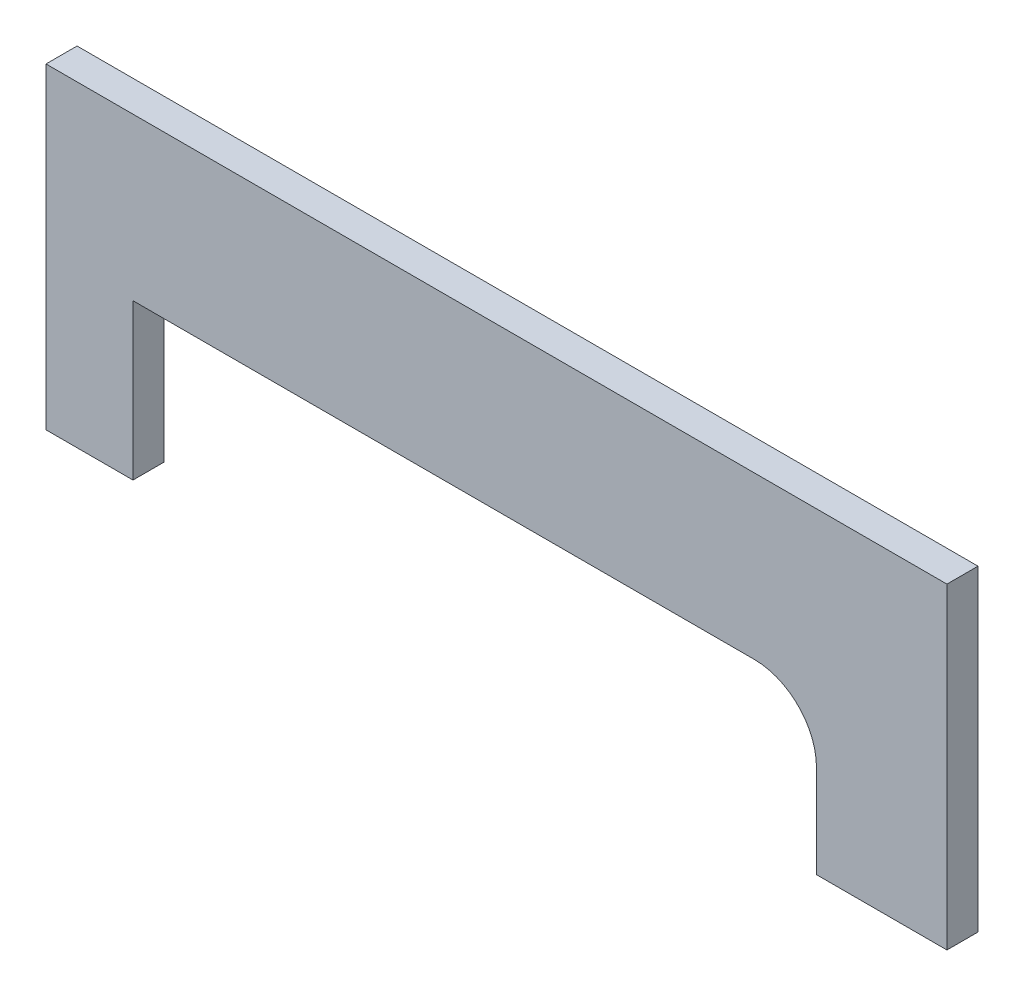
SolidWorks part; units mm, degrees
ref_plane "Plan de face" through (0, 0, 0) normal (0, 0, 1) x (1, 0, 0)
ref_plane "Plan de dessus" through (0, 0, 0) normal (0, 1, 0) x (1, 0, 0)
ref_plane "Plan de droite" through (0, 0, 0) normal (1, 0, 0) x (0, 0, -1)
sketch "Esquisse1" plane through (0, 0, 0) normal (0, 0, 1) x (1, 0, 0)
  line L0 (-48.7494, -48.1623) -> (-34.7494, -48.1623)
  line L1 (-48.7494, 2.8377) -> (96.2506, 2.8377)
  line L2 (-48.7494, 2.8377) -> (-48.7494, -48.1623)
  line L3 (-34.7494, -48.1623) -> (-34.7494, -23.1623)
  line L4 (96.2506, 2.8377) -> (96.2506, -48.1623)
  line L5 (-34.7494, -23.1623) -> (25.2506, -23.1623)
  line L6 (25.2506, -23.1623) -> (25.2506, -48.1623)
  line L7 (25.2506, -48.1623) -> (96.2506, -48.1623)
  dimension "D1" = 51
  dimension "D2" = 145
  dimension "D3" = 14
  dimension "D4" = 60
  dimension "D5" = 25
extrude "Extrusion1" add sketch "Esquisse1" along normal blind 5
sketch "Esquisse3" plane through (0, 0, 0) normal (0, 0, -1) x (-1, 0, 0)
  line L0 (-25.2506, -48.1623) -> (-96.2506, -48.1623) construction
  line L1 (-25.2506, -23.1623) -> (-65.2506, -23.1623)
  line L2 (-25.2506, -23.1623) -> (-25.2506, -48.1623)
  line L3 (-25.2506, -48.1623) -> (-75.2506, -48.1623)
  line L4 (-75.2506, -33.1623) -> (-75.2506, -48.1623)
  arc A0 (-75.2506, -33.1623) -> (-65.2506, -23.1623) centre (-65.2506, -33.1623) cw
  point P9 (-75.2506, -23.1623)
  dimension "D2" = 10
  dimension "D1" = 50
extrude "Extrusion2" cut sketch "Esquisse3" against normal up to next
